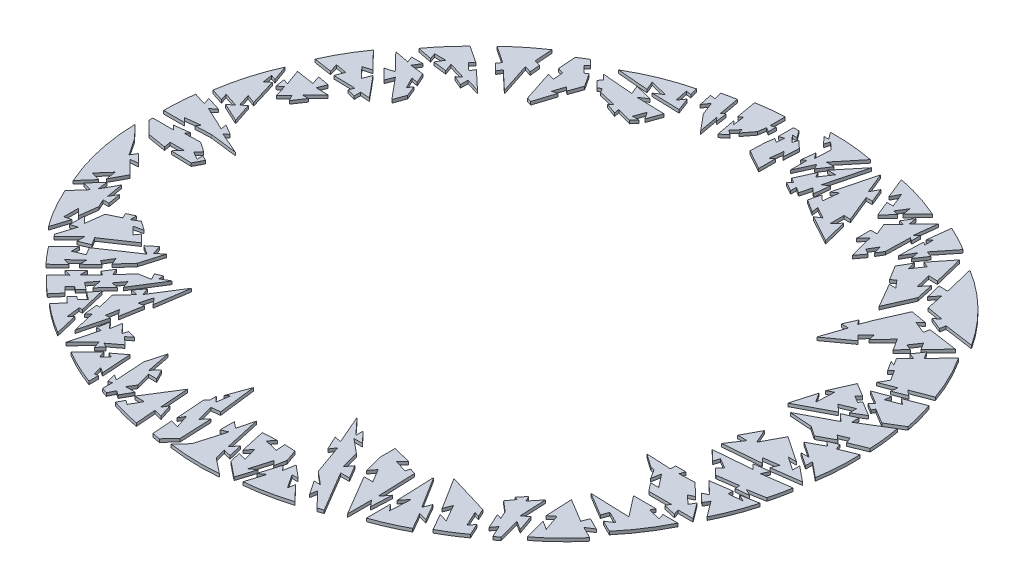
SolidWorks part; units mm, degrees
ref_plane "Front Plane" through (0, 0, 0) normal (0, 0, 1) x (1, 0, 0)
ref_plane "Top Plane" through (0, 0, 0) normal (0, 1, 0) x (1, 0, 0)
ref_plane "Right Plane" through (0, 0, 0) normal (1, 0, 0) x (0, 0, -1)
sketch "Sketch4" plane through (0, 0, 0) normal (0, 1, 0) x (1, 0, 0)
  line L0 (79.5359, 1089.8998) -> (71.878, 1117.1281)
  line L1 (73.9997, 1152.1973) -> (66.3418, 1179.4255)
  line L2 (66.3418, 1179.4255) -> (102.248, 1172.9243)
  line L3 (102.248, 1172.9243) -> (91.5541, 1145.5955)
  line L4 (91.5541, 1145.5955) -> (160.3382, 1144.0112)
  line L5 (160.3382, 1144.0112) -> (154.1634, 1128.2312)
  line L6 (154.1634, 1128.2312) -> (180.6697, 1121.1712)
  line L7 (180.6697, 1121.1712) -> (180.6697, 1142.2375)
  line L8 (73.9997, 1152.1973) -> (16.3638, 1160.9945)
  line L35 (210.6041, 1140.0847) -> (180.6697, 1142.2375)
  line L36 (71.878, 1117.1281) -> (107.7842, 1110.6269)
  line L37 (107.7842, 1110.6269) -> (97.0903, 1083.2981)
  line L38 (97.0903, 1083.2981) -> (135.6348, 1082.4103)
  line L39 (79.5359, 1089.8998) -> (21.9, 1098.6971)
  line L40 (21.9, 1098.6971) -> (40.3394, 1047.8857)
  line L41 (40.3394, 1047.8857) -> (23.558, 1054.1541)
  line L42 (23.558, 1054.1541) -> (28.1022, 1023.4113)
  line L43 (28.1022, 1023.4113) -> (43.8266, 1035.8446)
  line L44 (55.1591, 998.4828) -> (79.5359, 1023.4113)
  line L45 (79.5359, 1023.4113) -> (89.8311, 1004.6435)
  line L64 (89.8311, 1004.6435) -> (114.7462, 1041.0407)
  line L65 (114.7462, 1041.0407) -> (96.117, 1041.0407)
  line L66 (96.117, 1041.0407) -> (135.6348, 1082.4103)
  line L67 (43.8266, 1035.8446) -> (55.1591, 998.4828)
  line L68 (-9.812, 1090.6091) -> (8.6274, 1039.7977)
  line L69 (8.6274, 1039.7977) -> (-8.154, 1046.0661)
  line L70 (-8.154, 1046.0661) -> (-3.6098, 1015.3233)
  line L71 (-3.6098, 1015.3233) -> (12.1146, 1027.7566)
  line L72 (12.1146, 1027.7566) -> (38.0015, 942.4103)
  line L73 (38.0015, 942.4103) -> (9.8008, 952.6982)
  line L74 (9.8008, 952.6982) -> (22.6226, 912.6921)
  line L75 (22.6226, 912.6921) -> (38.0015, 925.5308)
  line L76 (38.0015, 925.5308) -> (58.1191, 864.5278)
  line L77 (58.1191, 864.5278) -> (-1.2858, 891.8241)
  line L78 (-1.2858, 891.8241) -> (16.2019, 906.4232)
  line L79 (16.2019, 906.4232) -> (-28.7199, 920.9974)
  line L80 (-28.7199, 920.9974) -> (-21.3292, 898.5866)
  line L81 (-21.3292, 898.5866) -> (-61.1515, 911.5063)
  line L82 (41.7553, 825.6716) -> (-17.6495, 852.9679)
  line L83 (-17.6495, 852.9679) -> (-0.1619, 867.567)
  line L84 (-0.1619, 867.567) -> (-45.0836, 882.1412)
  line L85 (-45.0836, 882.1412) -> (-37.693, 859.7304)
  line L86 (-37.693, 859.7304) -> (-77.5152, 872.6501)
  line L87 (41.7553, 825.6716) -> (59.7084, 816.3946)
  line L88 (59.7084, 816.3946) -> (55.819, 836.0191)
  line L89 (55.819, 836.0191) -> (88.8123, 816.3946)
  line L90 (88.8123, 816.3946) -> (76.112, 805.7921)
  line L91 (76.112, 805.7921) -> (146.473, 775.3267)
  line L92 (146.473, 775.3267) -> (59.7084, 785.9441)
  line L93 (59.7084, 785.9441) -> (8.8008, 783.9297)
  line L94 (8.8008, 783.9297) -> (17.1872, 795.589)
  line L95 (17.1872, 795.589) -> (-30.9924, 789.7594)
  line L96 (-30.9924, 789.7594) -> (-17.6495, 776.2204)
  line L97 (-17.6495, 776.2204) -> (-83.9589, 776.2204)
  line L98 (63.2013, 747.6353) -> (12.2938, 745.6208)
  line L99 (12.2938, 745.6208) -> (20.6801, 757.2802)
  line L100 (20.6801, 757.2802) -> (-27.4995, 751.4505)
  line L101 (-27.4995, 751.4505) -> (-14.1566, 737.9115)
  line L102 (-14.1566, 737.9115) -> (-80.466, 737.9115)
  line L103 (18.4006, 676.6175) -> (-41.5907, 686.5197)
  line L104 (-41.5907, 686.5197) -> (-80.2858, 725.7594)
  line L105 (18.4006, 676.6175) -> (14.8503, 698.4776)
  line L106 (14.8503, 698.4776) -> (59.312, 698.4776)
  line L107 (59.312, 698.4776) -> (40.2095, 676.6175)
  line L108 (40.2095, 676.6175) -> (105.5647, 675.0282)
  line L109 (121.2047, 705.1335) -> (105.5647, 675.0282)
  line L110 (104.6253, 713.0579) -> (104.6253, 694.5101)
  line L111 (104.6253, 694.5101) -> (79.6049, 708.9291)
  line L112 (79.6049, 708.9291) -> (94.4726, 725.943)
  line L113 (94.4726, 725.943) -> (63.2013, 747.6353)
  line L114 (121.2047, 705.1335) -> (104.6253, 713.0579)
  line L135 (-52.5566, 652.2053) -> (-91.2517, 691.445)
  line L136 (40.5682, 543.7111) -> (-2.8318, 587.3061)
  line L137 (-2.8318, 587.3061) -> (21.9174, 589.3977)
  line L138 (21.9174, 589.3977) -> (-4.7576, 616.1926)
  line L139 (-4.7576, 616.1926) -> (-16.1906, 597.7172)
  line L140 (-16.1906, 597.7172) -> (-52.5566, 652.2053)
  line L141 (-34.3736, 437.3354) -> (3.8844, 480.667)
  line L142 (3.8844, 480.667) -> (-25.1225, 488.2913)
  line L143 (-25.1225, 488.2913) -> (9.5428, 527.5539)
  line L144 (9.5428, 527.5539) -> (14.1648, 495.3898)
  line L145 (14.1648, 495.3898) -> (40.5682, 543.7111)
  line L146 (-19.5714, 396.3307) -> (18.6866, 439.6623)
  line L147 (18.6866, 439.6623) -> (-10.3203, 447.2866)
  line L148 (-10.3203, 447.2866) -> (24.345, 486.5492)
  line L149 (24.345, 486.5492) -> (28.967, 454.3851)
  line L150 (28.967, 454.3851) -> (55.3704, 502.7064)
  line L151 (55.3704, 502.7064) -> (64.4327, 448.5721)
  line L152 (64.4327, 448.5721) -> (78.7344, 472.4331)
  line L153 (78.7344, 472.4331) -> (85.5857, 431.5063)
  line L154 (85.5857, 431.5063) -> (67.0376, 431.5063)
  line L155 (67.0376, 431.5063) -> (78.7344, 406.2208)
  line L156 (78.7344, 406.2208) -> (71.5835, 348.2306)
  line L157 (71.5835, 348.2306) -> (50.9729, 368.1292)
  line L158 (50.9729, 368.1292) -> (50.9729, 321.2253)
  line L159 (50.9729, 321.2253) -> (71.5835, 327.4792)
  line L160 (71.5835, 327.4792) -> (53.6085, 270.245)
  line L161 (109.8229, 394.7287) -> (102.6721, 336.7385)
  line L162 (102.6721, 336.7385) -> (82.0614, 356.6371)
  line L163 (82.0614, 356.6371) -> (82.0614, 309.7332)
  line L164 (82.0614, 309.7332) -> (102.6721, 315.9871)
  line L165 (102.6721, 315.9871) -> (84.6971, 258.7529)
  line L166 (109.8229, 394.7287) -> (148.4258, 413.3028)
  line L167 (148.4258, 413.3028) -> (140.7503, 429.2549)
  line L168 (140.7503, 429.2549) -> (165.1674, 441.0033)
  line L169 (165.1674, 441.0033) -> (165.1674, 420.0142)
  line L170 (165.1674, 420.0142) -> (187.3968, 433.6883)
  line L171 (187.3968, 433.6883) -> (216.5305, 413.3028)
  line L172 (216.5305, 413.3028) -> (188.5529, 406.2811)
  line L173 (188.5529, 406.2811) -> (212.0257, 382.4073)
  line L174 (212.0257, 382.4073) -> (223.3551, 398.5985)
  line L175 (223.3551, 398.5985) -> (247.6934, 373.8445)
  line L176 (158.2649, 313.4244) -> (247.6934, 373.8445)
  line L177 (158.2649, 313.4244) -> (173.1358, 289.2494)
  line L178 (173.1358, 289.2494) -> (139.5784, 275.1033)
  line L179 (139.5784, 275.1033) -> (139.5784, 301.3369)
  line L180 (139.5784, 301.3369) -> (89.5954, 252.1934)
  line L181 (177.3283, 276.8624) -> (287.5603, 351.3379)
  line L182 (177.3283, 276.8624) -> (192.1992, 252.6874)
  line L183 (192.1992, 252.6874) -> (158.6418, 238.5412)
  line L184 (158.6418, 238.5412) -> (158.6418, 264.7749)
  line L185 (158.6418, 264.7749) -> (108.6588, 215.6313)
  line L186 (287.5603, 351.3379) -> (259.2555, 369.719)
  line L187 (259.2555, 369.719) -> (287.0565, 392.6928)
  line L188 (287.0565, 392.6928) -> (295.8178, 363.6402)
  line L189 (295.8178, 363.6402) -> (318.7295, 382.5737)
  line L190 (318.7295, 382.5737) -> (297.3156, 310.6221)
  line L191 (297.3156, 310.6221) -> (259.2555, 268.0309)
  line L192 (259.2555, 268.0309) -> (250.2294, 289.3265)
  line L193 (250.2294, 289.3265) -> (231.0892, 259.1338)
  line L194 (84.2949, 1279.2365) -> (138.6323, 1222.9248)
  line L195 (138.6323, 1222.9248) -> (111.4636, 1214.9972)
  line L196 (111.4636, 1214.9972) -> (143.6719, 1181.6185)
  line L197 (143.6719, 1181.6185) -> (154.1634, 1207.9843)
  line L198 (154.1634, 1207.9843) -> (210.6041, 1140.0847)
  line L199 (231.0892, 259.1338) -> (244.7359, 250.4826)
  line L200 (244.7359, 250.4826) -> (207.6163, 215.6313)
  line L201 (207.6163, 215.6313) -> (207.6163, 238.5412)
  line L202 (207.6163, 238.5412) -> (170.9902, 204.1532)
  line L203 (170.9902, 204.1532) -> (192.2281, 197.8325)
  line L204 (192.2281, 197.8325) -> (153.9045, 161.9312)
  line L205 (327.7031, 282.0513) -> (364.7513, 288.7164)
  line L206 (364.7513, 288.7164) -> (354.124, 308.7117)
  line L207 (354.124, 308.7117) -> (375.3188, 317.2744)
  line L208 (375.3188, 317.2744) -> (375.3188, 302.0466)
  line L209 (375.3188, 302.0466) -> (402.175, 317.2744)
  line L210 (327.7031, 282.0513) -> (289.643, 239.4601)
  line L211 (289.643, 239.4601) -> (280.617, 260.7557)
  line L212 (280.617, 260.7557) -> (261.4767, 230.563)
  line L213 (261.4767, 230.563) -> (275.1235, 221.9118)
  line L214 (275.1235, 221.9118) -> (238.0039, 187.0605)
  line L215 (238.0039, 187.0605) -> (238.0039, 209.9704)
  line L216 (238.0039, 209.9704) -> (201.3777, 175.5824)
  line L217 (201.3777, 175.5824) -> (222.6156, 169.2617)
  line L218 (222.6156, 169.2617) -> (184.292, 133.3604)
  line L219 (402.175, 317.2744) -> (341.8275, 221.9118)
  line L220 (341.8275, 221.9118) -> (333.1879, 244.6003)
  line L221 (333.1879, 244.6003) -> (311.4804, 216.0333)
  line L222 (311.4804, 216.0333) -> (332.3107, 211.7006)
  line L223 (332.3107, 211.7006) -> (294.4375, 171.3508)
  line L224 (287.3953, 201.1846) -> (294.4375, 171.3508)
  line L225 (287.3953, 201.1846) -> (265.9814, 173.004)
  line L226 (265.9814, 173.004) -> (288.2043, 156.1173)
  line L227 (288.2043, 156.1173) -> (271.5121, 138.3335)
  line L228 (271.5121, 138.3335) -> (261.4767, 145.9592)
  line L229 (261.4767, 145.9592) -> (246.1918, 129.6748)
  line L230 (246.1918, 129.6748) -> (264.3109, 112.6678)
  line L231 (264.3109, 112.6678) -> (238.114, 81.973)
  line L232 (318.166, 177.3401) -> (337.8259, 94.0532)
  line L233 (318.166, 177.3401) -> (296.7522, 149.1595)
  line L234 (296.7522, 149.1595) -> (318.975, 132.2728)
  line L235 (318.975, 132.2728) -> (302.2828, 114.489)
  line L236 (302.2828, 114.489) -> (292.2474, 122.1147)
  line L237 (292.2474, 122.1147) -> (276.9626, 105.8303)
  line L238 (276.9626, 105.8303) -> (295.0817, 88.8234)
  line L239 (295.0817, 88.8234) -> (268.8848, 58.1285)
  line L240 (337.8259, 94.0532) -> (327.9151, 94.0532)
  line L241 (327.9151, 94.0532) -> (332.8705, 49.6725)
  line L242 (332.8705, 49.6725) -> (344.9741, 63.7705)
  line L243 (344.9741, 63.7705) -> (362.023, -8.4551)
  line L244 (440.4983, 119.8912) -> (434.3623, 83.8629)
  line L245 (434.3623, 83.8629) -> (416.9707, 104.6379)
  line L246 (416.9707, 104.6379) -> (410.558, 66.9847)
  line L247 (410.558, 66.9847) -> (425.6665, 66.9847)
  line L248 (425.6665, 66.9847) -> (402.5678, -22.3111)
  line L249 (454.3684, 31.6376) -> (402.5678, -22.3111)
  line L250 (454.3684, 31.6376) -> (461.7886, 9.1427)
  line L251 (461.7886, 9.1427) -> (480.2454, 28.3649)
  line L252 (480.2454, 28.3649) -> (465.6489, 35.8165)
  line L253 (465.6489, 35.8165) -> (503.6435, 64.677)
  line L254 (503.6435, 64.677) -> (480.2454, 87.1434)
  line L255 (480.2454, 87.1434) -> (498.0043, 100.633)
  line L256 (498.0043, 100.633) -> (472.9472, 108.2587)
  line L257 (472.9472, 108.2587) -> (467.859, 91.5396)
  line L258 (467.859, 91.5396) -> (440.4983, 119.8912)
  line L259 (453.5868, 328.4896) -> (393.2394, 233.127)
  line L260 (393.2394, 233.127) -> (384.5998, 255.8155)
  line L261 (384.5998, 255.8155) -> (362.8923, 227.2485)
  line L262 (362.8923, 227.2485) -> (383.7226, 222.9158)
  line L263 (383.7226, 222.9158) -> (345.8494, 182.566)
  line L264 (345.8494, 182.566) -> (358.4671, 129.1129)
  line L265 (358.4671, 129.1129) -> (348.5562, 129.1129)
  line L266 (348.5562, 129.1129) -> (353.5116, 84.7321)
  line L267 (353.5116, 84.7321) -> (365.6153, 98.8302)
  line L268 (365.6153, 98.8302) -> (382.6642, 26.6045)
  line L269 (453.5868, 328.4896) -> (437.3752, 221.1856)
  line L270 (437.3752, 221.1856) -> (420.1363, 241.7782)
  line L271 (420.1363, 241.7782) -> (408.781, 201.354)
  line L272 (408.781, 201.354) -> (426.7307, 204.8352)
  line L273 (426.7307, 204.8352) -> (414.4587, 132.7786)
  line L274 (414.4587, 132.7786) -> (397.0671, 153.5535)
  line L275 (397.0671, 153.5535) -> (390.6544, 115.9004)
  line L276 (390.6544, 115.9004) -> (405.7629, 115.9004)
  line L277 (405.7629, 115.9004) -> (382.6642, 26.6045)
  line L278 (489.7421, 12.2739) -> (437.9415, -41.6748)
  line L279 (489.7421, 12.2739) -> (497.1624, -10.221)
  line L280 (497.1624, -10.221) -> (515.6191, 9.0012)
  line L281 (515.6191, 9.0012) -> (501.0227, 16.4528)
  line L282 (501.0227, 16.4528) -> (539.0172, 45.3134)
  line L283 (539.0172, 45.3134) -> (545.1565, -48.1271)
  line L284 (545.1565, -48.1271) -> (528.2486, -37.3245)
  line L285 (528.2486, -37.3245) -> (535.5641, -65.1355)
  line L286 (535.5641, -65.1355) -> (546.7364, -62.1968)
  line L287 (546.7364, -62.1968) -> (546.7364, -93.4831)
  line L288 (597.756, 108.0004) -> (581.0328, 47.2511)
  line L289 (581.0328, 47.2511) -> (587.1721, -46.1894)
  line L290 (587.1721, -46.1894) -> (570.2643, -35.3868)
  line L291 (570.2643, -35.3868) -> (577.5797, -63.1978)
  line L292 (577.5797, -63.1978) -> (588.752, -60.259)
  line L293 (588.752, -60.259) -> (588.752, -91.5454)
  line L294 (606.8822, -97.9517) -> (617.9056, -75.6525)
  line L295 (617.9056, -75.6525) -> (631.3095, -85.1148)
  line L296 (631.3095, -85.1148) -> (651.3371, -49.9464)
  line L297 (651.3371, -49.9464) -> (620.7429, -49.9464)
  line L298 (620.7429, -49.9464) -> (635.6983, -26.1224)
  line L299 (597.756, 108.0004) -> (612.6601, 32.4885)
  line L300 (612.6601, 32.4885) -> (632.4593, 53.6124)
  line L301 (632.4593, 53.6124) -> (648.8369, 21.3093)
  line L302 (648.8369, 21.3093) -> (622.5597, 21.3093)
  line L303 (622.5597, 21.3093) -> (635.6983, -26.1224)
  line L304 (647.7806, -109.7054) -> (658.804, -87.4062)
  line L305 (658.804, -87.4062) -> (672.2079, -96.8685)
  line L306 (672.2079, -96.8685) -> (692.2355, -61.7001)
  line L307 (692.2355, -61.7001) -> (661.6413, -61.7001)
  line L308 (661.6413, -61.7001) -> (726.6499, 41.8587)
  line L309 (726.6499, 41.8587) -> (733.4955, -51.4908)
  line L310 (733.4955, -51.4908) -> (744.7171, -31.7858)
  line L311 (744.7171, -31.7858) -> (758.6307, -74.9515)
  line L312 (758.6307, -74.9515) -> (733.4955, -68.6384)
  line L313 (733.4955, -68.6384) -> (738.2376, -133.3031)
  line L314 (782.5526, 38.6884) -> (789.3982, -54.6612)
  line L315 (789.3982, -54.6612) -> (800.6198, -34.9561)
  line L316 (800.6198, -34.9561) -> (814.5334, -78.1219)
  line L317 (814.5334, -78.1219) -> (789.3982, -71.8088)
  line L318 (789.3982, -71.8088) -> (794.1403, -136.4735)
  line L319 (782.5526, 38.6884) -> (792.499, 47.8472)
  line L320 (792.499, 47.8472) -> (792.499, 68.283)
  line L321 (792.499, 68.283) -> (807.9228, 51.5329)
  line L322 (807.9228, 51.5329) -> (814.5334, 93.0764)
  line L323 (814.5334, 93.0764) -> (802.5788, 82.0683)
  line L324 (802.5788, 82.0683) -> (827.7928, 151.8613)
  line L325 (827.7928, 151.8613) -> (842.5112, 32.327)
  line L326 (842.5112, 32.327) -> (814.5334, 28.8821)
  line L327 (814.5334, 28.8821) -> (828.5223, -23.2073)
  line L328 (828.5223, -23.2073) -> (846.939, -3.6329)
  line L329 (846.939, -3.6329) -> (851.2656, -106.4695)
  line L330 (851.2656, -106.4695) -> (819.0982, -140.659)
  line L331 (884.602, -102.3334) -> (852.4346, -136.523)
  line L332 (1011.3991, -140.9469) -> (963.0536, -102.3334)
  line L333 (963.0536, -102.3334) -> (954.3483, -67.6727)
  line L334 (954.3483, -67.6727) -> (979.2244, -73.9858)
  line L335 (979.2244, -73.9858) -> (968.3831, -30.8201)
  line L336 (968.3831, -30.8201) -> (951.1449, -52.4029)
  line L337 (951.1449, -52.4029) -> (925.3875, 63.3256)
  line L338 (925.3875, 63.3256) -> (911.9868, 10.5214)
  line L339 (911.9868, 10.5214) -> (891.5946, 26.8085)
  line L340 (891.5946, 26.8085) -> (891.5946, -19.0713)
  line L341 (891.5946, -19.0713) -> (911.9868, -9.6421)
  line L342 (911.9868, -9.6421) -> (884.602, -102.3334)
  line L343 (1044.5789, -126.9573) -> (996.2333, -88.3438)
  line L344 (996.2333, -88.3438) -> (987.5281, -53.6831)
  line L345 (987.5281, -53.6831) -> (1012.4042, -59.9962)
  line L346 (1012.4042, -59.9962) -> (1001.5629, -16.8305)
  line L347 (1001.5629, -16.8305) -> (984.3247, -38.4133)
  line L348 (984.3247, -38.4133) -> (966.6948, 40.7981)
  line L349 (1069.9912, 42.4) -> (1083.4627, 4.3475)
  line L350 (1083.4627, 4.3475) -> (1076.7177, -32.1852)
  line L351 (1076.7177, -32.1852) -> (1063.0141, -16.8305)
  line L352 (1063.0141, -16.8305) -> (1043.786, -81.9132)
  line L353 (1043.786, -81.9132) -> (1063.0141, -68.0416)
  line L354 (1063.0141, -68.0416) -> (1044.5789, -126.9573)
  line L355 (966.6948, 40.7981) -> (1012.4042, 44.0018)
  line L356 (1012.4042, 44.0018) -> (996.2333, 24.5109)
  line L357 (996.2333, 24.5109) -> (1038.0939, 14.4927)
  line L358 (1038.0939, 14.4927) -> (1036.0257, 44.0018)
  line L359 (1036.0257, 44.0018) -> (1069.9912, 42.4)
  line L360 (1110.8077, 5.503) -> (1104.0626, -31.0296)
  line L361 (1104.0626, -31.0296) -> (1090.359, -15.6749)
  line L362 (1090.359, -15.6749) -> (1071.131, -80.7577)
  line L363 (1071.131, -80.7577) -> (1090.359, -66.886)
  line L364 (1090.359, -66.886) -> (1071.9239, -125.8017)
  line L365 (1110.8077, 5.503) -> (1151.1002, -28.12)
  line L366 (1151.1002, -28.12) -> (1130.954, -28.12)
  line L367 (1130.954, -28.12) -> (1160.0657, -71.2953)
  line L368 (1160.0657, -71.2953) -> (1164.0515, -49.7077)
  line L369 (1164.0515, -49.7077) -> (1210.4222, -98.0808)
  line L370 (1076.2683, 235.2613) -> (1116.7409, 141.4578)
  line L371 (1116.7409, 141.4578) -> (1095.947, 145.297)
  line L372 (1095.947, 145.297) -> (1116.7409, 100.7247)
  line L373 (1116.7409, 100.7247) -> (1129.5655, 119.4831)
  line L374 (1129.5655, 119.4831) -> (1163.4977, 23.6366)
  line L375 (1163.4977, 23.6366) -> (1203.7902, -9.9864)
  line L376 (1203.7902, -9.9864) -> (1183.644, -9.9864)
  line L377 (1183.644, -9.9864) -> (1212.7557, -53.1617)
  line L378 (1212.7557, -53.1617) -> (1216.7415, -31.574)
  line L379 (1216.7415, -31.574) -> (1263.1122, -79.9472)
  line L380 (1280.3407, -74.2932) -> (1203.7902, 54.9793)
  line L381 (1203.7902, 54.9793) -> (1231.8985, 54.9793)
  line L382 (1231.8985, 54.9793) -> (1206.6199, 97.6679)
  line L383 (1206.6199, 97.6679) -> (1190.6172, 76.3236)
  line L384 (1190.6172, 76.3236) -> (1175.4344, 133.7856)
  line L385 (1175.4344, 133.7856) -> (1129.5655, 171.5201)
  line L386 (1129.5655, 171.5201) -> (1156.7526, 171.5201)
  line L387 (1156.7526, 171.5201) -> (1123.821, 206.8244)
  line L388 (1123.821, 206.8244) -> (1123.821, 183.3976)
  line L389 (1123.821, 183.3976) -> (1076.2683, 235.2613)
  line L390 (1328.2533, -47.5513) -> (1251.7029, 81.7211)
  line L391 (1251.7029, 81.7211) -> (1279.8112, 81.7211)
  line L392 (1279.8112, 81.7211) -> (1254.5325, 124.4097)
  line L393 (1254.5325, 124.4097) -> (1238.5299, 103.0654)
  line L394 (1238.5299, 103.0654) -> (1223.3471, 160.5274)
  line L395 (1328.2533, -47.5513) -> (1328.2533, 29.2005)
  line L396 (1328.2533, 29.2005) -> (1345.2819, 9.4955)
  line L397 (1345.2819, 9.4955) -> (1348.3643, 76.0791)
  line L398 (1348.3643, 76.0791) -> (1328.2533, 50.3785)
  line L399 (1328.2533, 50.3785) -> (1323.5175, 172.0388)
  line L400 (1323.5175, 172.0388) -> (1305.4299, 177.4734)
  line L401 (1305.4299, 177.4734) -> (1301.2732, 163.6391)
  line L402 (1301.2732, 163.6391) -> (1260.6684, 175.8392)
  line L403 (1260.6684, 175.8392) -> (1280.9301, 195.2907)
  line L404 (1280.9301, 195.2907) -> (1223.3471, 210.1394)
  line L405 (1223.3471, 160.5274) -> (1223.3471, 210.1394)
  line L406 (1370.2147, -28.8543) -> (1370.2147, 47.8976)
  line L407 (1370.2147, 47.8976) -> (1387.2432, 28.1926)
  line L408 (1387.2432, 28.1926) -> (1390.3257, 94.7762)
  line L409 (1390.3257, 94.7762) -> (1370.2147, 69.0756)
  line L410 (1370.2147, 69.0756) -> (1365.4788, 190.7359)
  line L411 (1365.4788, 190.7359) -> (1429.0622, 89.239)
  line L412 (1429.0622, 89.239) -> (1439.1849, 115.1807)
  line L413 (1439.1849, 115.1807) -> (1470.0401, 61.4844)
  line L414 (1470.0401, 61.4844) -> (1442.7514, 69.0756)
  line L415 (1442.7514, 69.0756) -> (1473.0067, 16.4233)
  line L416 (1400.9661, 220.3988) -> (1464.5495, 118.9019)
  line L417 (1464.5495, 118.9019) -> (1474.6721, 144.8436)
  line L418 (1474.6721, 144.8436) -> (1505.5274, 91.1473)
  line L419 (1505.5274, 91.1473) -> (1478.2386, 98.7385)
  line L420 (1478.2386, 98.7385) -> (1508.494, 46.0863)
  line L421 (1532.7607, 180.7996) -> (1544.5319, 155.1339)
  line L422 (1544.5319, 155.1339) -> (1528.505, 160.3638)
  line L423 (1528.505, 160.3638) -> (1550.7762, 111.8042)
  line L424 (1550.7762, 111.8042) -> (1564.4925, 130.0811)
  line L425 (1564.4925, 130.0811) -> (1581.7569, 92.4382)
  line L426 (1532.7607, 180.7996) -> (1400.9661, 220.3988)
  line L427 (1574.3271, 210.7666) -> (1586.0983, 185.101)
  line L428 (1586.0983, 185.101) -> (1570.0714, 190.3308)
  line L429 (1570.0714, 190.3308) -> (1592.3426, 141.7712)
  line L430 (1592.3426, 141.7712) -> (1606.0589, 160.0481)
  line L431 (1606.0589, 160.0481) -> (1623.3233, 122.4052)
  line L432 (1574.3271, 210.7666) -> (1541.8504, 238.4099)
  line L433 (1606.0589, 307.483) -> (1578.4235, 273.6177)
  line L434 (1578.4235, 273.6177) -> (1570.0714, 290.5504)
  line L435 (1570.0714, 290.5504) -> (1550.0808, 266.0532)
  line L436 (1550.0808, 266.0532) -> (1560.0761, 263.6974)
  line L437 (1560.0761, 263.6974) -> (1541.8504, 238.4099)
  line L438 (1638.5754, 133.8409) -> (1620.1147, 202.7368)
  line L439 (1620.1147, 202.7368) -> (1648.0171, 185.101)
  line L440 (1648.0171, 185.101) -> (1629.3451, 238.4099)
  line L441 (1629.3451, 238.4099) -> (1610.1228, 222.8264)
  line L442 (1610.1228, 222.8264) -> (1606.0589, 307.483)
  line L443 (1679.6101, 176.3637) -> (1661.1494, 245.2596)
  line L444 (1661.1494, 245.2596) -> (1689.0517, 227.6238)
  line L445 (1689.0517, 227.6238) -> (1670.3797, 280.9328)
  line L446 (1670.3797, 280.9328) -> (1651.1574, 265.3493)
  line L447 (1651.1574, 265.3493) -> (1647.0935, 350.0059)
  line L448 (1647.0935, 350.0059) -> (1721.9473, 305.0948)
  line L449 (1721.9473, 305.0948) -> (1730.3224, 327.5503)
  line L450 (1730.3224, 327.5503) -> (1768.1103, 308.5761)
  line L451 (1768.1103, 308.5761) -> (1744.1218, 292.8887)
  line L452 (1744.1218, 292.8887) -> (1781.644, 274.0478)
  line L453 (1735.6758, 460.2851) -> (1786.9133, 394.4206)
  line L454 (1786.9133, 394.4206) -> (1660.8221, 398.9075)
  line L455 (1882.5379, 455.3618) -> (1834.6764, 455.3618)
  line L456 (1834.6764, 455.3618) -> (1840.4702, 437.6367)
  line L457 (1840.4702, 437.6367) -> (1800.7038, 446.4993)
  line L458 (1800.7038, 446.4993) -> (1807.8143, 460.2851)
  line L459 (1807.8143, 460.2851) -> (1735.6758, 460.2851)
  line L460 (1660.8221, 398.9075) -> (1735.6758, 353.9964)
  line L461 (1735.6758, 353.9964) -> (1744.0509, 376.4519)
  line L462 (1744.0509, 376.4519) -> (1781.8388, 357.4777)
  line L463 (1781.8388, 357.4777) -> (1757.8503, 341.7903)
  line L464 (1757.8503, 341.7903) -> (1795.3726, 322.9494)
  line L465 (1684.3269, 567.2579) -> (1696.442, 565.488)
  line L466 (1696.442, 565.488) -> (1714.701, 536.1045)
  line L467 (1714.701, 536.1045) -> (1720.341, 565.488)
  line L468 (1720.341, 565.488) -> (1753.0451, 523.4477)
  line L469 (1753.0451, 523.4477) -> (1727.1065, 523.4477)
  line L470 (1727.1065, 523.4477) -> (1747.5966, 497.1081)
  line L471 (1641.0111, 597.6249) -> (1684.3269, 567.2579)
  line L472 (1894.4587, 492.1848) -> (1846.5972, 492.1848)
  line L473 (1846.5972, 492.1848) -> (1852.391, 474.4597)
  line L474 (1852.391, 474.4597) -> (1812.6246, 483.3223)
  line L475 (1812.6246, 483.3223) -> (1819.7351, 497.1081)
  line L476 (1819.7351, 497.1081) -> (1747.5966, 497.1081)
  line L477 (1894.4587, 492.1848) -> (1857.3442, 541.8288)
  line L478 (1857.3442, 541.8288) -> (1846.5972, 523.4477)
  line L479 (1846.5972, 523.4477) -> (1819.7351, 548.8505)
  line L480 (1819.7351, 548.8505) -> (1837.3798, 557.4161)
  line L481 (1837.3798, 557.4161) -> (1796.8762, 595.7194)
  line L482 (1641.0111, 597.6249) -> (1720.341, 593.8139)
  line L483 (1720.341, 593.8139) -> (1720.341, 610.2642)
  line L484 (1720.341, 610.2642) -> (1753.0451, 610.2642)
  line L485 (1753.0451, 610.2642) -> (1747.5966, 593.8139)
  line L486 (1747.5966, 593.8139) -> (1796.8762, 595.7194)
  line L487 (1911.8649, 519.3218) -> (1874.7505, 568.9658)
  line L488 (1874.7505, 568.9658) -> (1864.0034, 550.5846)
  line L489 (1864.0034, 550.5846) -> (1837.1414, 575.9875)
  line L490 (1837.1414, 575.9875) -> (1854.7861, 584.553)
  line L491 (1854.7861, 584.553) -> (1814.2825, 622.8564)
  line L492 (1881.8619, 632.234) -> (1881.8619, 616.7978)
  line L493 (1881.8619, 616.7978) -> (1924.8748, 620.9509)
  line L494 (1924.8748, 620.9509) -> (1903.3683, 632.234)
  line L495 (1903.3683, 632.234) -> (1958.6347, 641.7743)
  line L496 (1814.2825, 622.8564) -> (1881.8619, 632.234)
  line L497 (1810.1127, 648.9588) -> (1790.1081, 667.8767)
  line L498 (1790.1081, 667.8767) -> (1804.5325, 683.1297)
  line L499 (1804.5325, 683.1297) -> (1772.0136, 702.1427)
  line L500 (1772.0136, 702.1427) -> (1766.2816, 683.1297)
  line L501 (1766.2816, 683.1297) -> (1733.5774, 714.0573)
  line L502 (1877.692, 658.3364) -> (1877.692, 642.9002)
  line L503 (1877.692, 642.9002) -> (1920.705, 647.0533)
  line L504 (1920.705, 647.0533) -> (1899.1985, 658.3364)
  line L505 (1899.1985, 658.3364) -> (1954.4649, 667.8767)
  line L506 (1810.1127, 648.9588) -> (1877.692, 658.3364)
  line L507 (1969.4631, 737.0668) -> (1877.692, 724.3323)
  line L508 (1877.692, 724.3323) -> (1887.4094, 746.8746)
  line L509 (1887.4094, 746.8746) -> (1838.2978, 740.0597)
  line L510 (1838.2978, 740.0597) -> (1853.376, 724.3323)
  line L511 (1853.376, 724.3323) -> (1733.5774, 714.0573)
  line L512 (1967.5266, 769.0904) -> (1875.7555, 756.3558)
  line L513 (1875.7555, 756.3558) -> (1885.4729, 778.8982)
  line L514 (1885.4729, 778.8982) -> (1836.3612, 772.0832)
  line L515 (1836.3612, 772.0832) -> (1851.4395, 756.3558)
  line L516 (1851.4395, 756.3558) -> (1731.6409, 746.0808)
  line L517 (1731.6409, 746.0808) -> (1764.345, 794.5808)
  line L518 (1764.345, 794.5808) -> (1734.8449, 794.5808)
  line L519 (1734.8449, 794.5808) -> (1764.345, 850.0748)
  line L520 (1764.345, 850.0748) -> (1784.5305, 805.8321)
  line L521 (1784.5305, 805.8321) -> (1819.1823, 871.0172)
  line L522 (1819.1823, 871.0172) -> (1901.8115, 815.2994)
  line L523 (1901.8115, 815.2994) -> (1875.7555, 815.2994)
  line L524 (1875.7555, 815.2994) -> (1918.7684, 786.2953)
  line L525 (1918.7684, 786.2953) -> (1918.7684, 808.8789)
  line L526 (1918.7684, 808.8789) -> (1967.5266, 769.0904)
  line L527 (1860.1835, 881.5515) -> (1910.5554, 847.585)
  line L528 (1910.5554, 847.585) -> (1884.4995, 847.585)
  line L529 (1884.4995, 847.585) -> (1927.5124, 818.5809)
  line L530 (1927.5124, 818.5809) -> (1927.5124, 841.1645)
  line L531 (1927.5124, 841.1645) -> (1976.2706, 801.376)
  line L532 (1984.2379, 936.4209) -> (1930.8447, 914.4706)
  line L533 (1930.8447, 914.4706) -> (1923.471, 932.4069)
  line L534 (1923.471, 932.4069) -> (1894.2169, 920.3803)
  line L535 (1894.2169, 920.3803) -> (1908.8439, 908.0157)
  line L536 (1908.8439, 908.0157) -> (1860.1835, 881.5515)
  line L537 (1725.9126, 964.0161) -> (1832.2092, 1019.9958)
  line L538 (1832.2092, 1019.9958) -> (1808.8399, 1041.0191)
  line L539 (1808.8399, 1041.0191) -> (1851.2944, 1058.694)
  line L540 (1851.2944, 1058.694) -> (1851.2944, 1035.4058)
  line L541 (1851.2944, 1035.4058) -> (1889.6326, 1058.6564)
  line L542 (1725.9126, 964.0161) -> (1747.8819, 1041.0191)
  line L543 (1747.8819, 1041.0191) -> (1768.0296, 1010.8859)
  line L544 (1768.0296, 1010.8859) -> (1770.6085, 1068.8342)
  line L545 (1770.6085, 1068.8342) -> (1751.9106, 1058.694)
  line L546 (1751.9106, 1058.694) -> (1782.8644, 1129.0422)
  line L547 (1782.8644, 1129.0422) -> (1826.4846, 1102.729)
  line L548 (1826.868, 937.1464) -> (1859.1251, 915.395)
  line L549 (1755.7934, 941.8592) -> (1826.868, 937.1464)
  line L550 (1983.1796, 970.2644) -> (1929.7864, 948.3141)
  line L551 (1929.7864, 948.3141) -> (1922.4127, 966.2504)
  line L552 (1922.4127, 966.2504) -> (1893.1585, 954.2238)
  line L553 (1893.1585, 954.2238) -> (1907.7856, 941.8592)
  line L554 (1907.7856, 941.8592) -> (1859.1251, 915.395)
  line L555 (1755.7934, 941.8592) -> (1862.09, 997.8388)
  line L556 (1862.09, 997.8388) -> (1838.7207, 1018.8621)
  line L557 (1838.7207, 1018.8621) -> (1881.1752, 1036.5371)
  line L558 (1881.1752, 1036.5371) -> (1881.1752, 1013.2488)
  line L559 (1881.1752, 1013.2488) -> (1971.7274, 1068.1652)
  line L560 (1826.4846, 1102.729) -> (1814.1661, 1090.3221)
  line L561 (1814.1661, 1090.3221) -> (1835.702, 1077.331)
  line L562 (1835.702, 1077.331) -> (1841.8313, 1087.4917)
  line L563 (1841.8313, 1087.4917) -> (1889.6326, 1058.6564)
  line L564 (1824.3671, 1129.5565) -> (1873.712, 1148.4939)
  line L565 (1873.712, 1148.4939) -> (1870.7471, 1127.5982)
  line L566 (1870.7471, 1127.5982) -> (1912.9471, 1143.7936)
  line L567 (1912.9471, 1143.7936) -> (1895.0631, 1158.0306)
  line L568 (1895.0631, 1158.0306) -> (1958.8215, 1182.4995)
  line L569 (1931.1353, 1059.1708) -> (1983.3494, 1090.8365)
  line L570 (1824.3671, 1129.5565) -> (1867.9873, 1103.2434)
  line L571 (1867.9873, 1103.2434) -> (1855.6688, 1090.8365)
  line L572 (1855.6688, 1090.8365) -> (1877.2047, 1077.8453)
  line L573 (1877.2047, 1077.8453) -> (1883.334, 1088.0061)
  line L574 (1883.334, 1088.0061) -> (1931.1353, 1059.1708)
  line L575 (1874.1404, 1361.7653) -> (1820.1334, 1305.9795)
  line L576 (1820.1334, 1305.9795) -> (1806.4117, 1327.5541)
  line L577 (1806.4117, 1327.5541) -> (1784.8832, 1295.7166)
  line L578 (1784.8832, 1295.7166) -> (1803.5386, 1288.325)
  line L579 (1803.5386, 1288.325) -> (1776.5149, 1260.4113)
  line L580 (1776.5149, 1260.4113) -> (1790.0268, 1239.1666)
  line L581 (1790.0268, 1239.1666) -> (1775.5733, 1244.8932)
  line L582 (1775.5733, 1244.8932) -> (1795.721, 1213.2149)
  line L583 (1795.721, 1213.2149) -> (1806.4083, 1224.2542)
  line L584 (1806.4083, 1224.2542) -> (1826.8945, 1192.0437)
  line L585 (1826.8945, 1192.0437) -> (1810.5558, 1163.5697)
  line L586 (1810.5558, 1163.5697) -> (1859.9007, 1182.5071)
  line L587 (1859.9007, 1182.5071) -> (1856.9358, 1161.6114)
  line L588 (1856.9358, 1161.6114) -> (1899.1358, 1177.8067)
  line L589 (1899.1358, 1177.8067) -> (1881.2518, 1192.0437)
  line L590 (1881.2518, 1192.0437) -> (1945.0102, 1216.5127)
  line L591 (1671.3801, 1415.9719) -> (1723.861, 1407.0041)
  line L592 (1723.861, 1407.0041) -> (1707.3941, 1392.4435)
  line L593 (1707.3941, 1392.4435) -> (1746.7719, 1376.8414)
  line L594 (1746.7719, 1376.8414) -> (1749.859, 1394.908)
  line L595 (1749.859, 1394.908) -> (1844.3974, 1381.4941)
  line L596 (1844.3974, 1381.4941) -> (1790.3903, 1325.7082)
  line L597 (1790.3903, 1325.7082) -> (1776.6687, 1347.2829)
  line L598 (1776.6687, 1347.2829) -> (1755.1401, 1315.4453)
  line L599 (1755.1401, 1315.4453) -> (1773.7955, 1308.0537)
  line L600 (1773.7955, 1308.0537) -> (1746.7719, 1280.14)
  line L601 (1671.3801, 1415.9719) -> (1633.5386, 1329.8668)
  line L602 (1746.7719, 1280.14) -> (1723.861, 1316.1629)
  line L603 (1723.861, 1316.1629) -> (1679.4776, 1270.3177)
  line L604 (1679.4776, 1270.3177) -> (1675.2335, 1290.345)
  line L605 (1675.2335, 1290.345) -> (1649.8157, 1264.09)
  line L606 (1649.8157, 1264.09) -> (1665.5881, 1248.8206)
  line L607 (1665.5881, 1248.8206) -> (1588.8569, 1193.4066)
  line L608 (1588.8569, 1193.4066) -> (1614.457, 1269.076)
  line L609 (1614.457, 1269.076) -> (1591.9304, 1269.076)
  line L610 (1591.9304, 1269.076) -> (1609.0603, 1308.0537)
  line L611 (1609.0603, 1308.0537) -> (1619.7584, 1293.2403)
  line L612 (1619.7584, 1293.2403) -> (1633.5386, 1329.8668)
  line L613 (1648.7206, 1623.6934) -> (1671.6418, 1529.6096)
  line L614 (1671.6418, 1529.6096) -> (1643.2463, 1530.3543)
  line L615 (1643.2463, 1530.3543) -> (1655.0175, 1482.0374)
  line L616 (1655.0175, 1482.0374) -> (1674.9781, 1507.1112)
  line L617 (1674.9781, 1507.1112) -> (1686.5621, 1452.448)
  line L618 (1686.5621, 1452.448) -> (1739.0431, 1443.4802)
  line L619 (1739.0431, 1443.4802) -> (1722.5762, 1428.9197)
  line L620 (1722.5762, 1428.9197) -> (1761.9539, 1413.3176)
  line L621 (1761.9539, 1413.3176) -> (1765.0411, 1431.3841)
  line L622 (1765.0411, 1431.3841) -> (1859.5794, 1417.9702)
  line L623 (1603.7365, 1378.2365) -> (1559.0549, 1455.3737)
  line L624 (1559.0549, 1455.3737) -> (1579.6899, 1455.3737)
  line L625 (1579.6899, 1455.3737) -> (1559.0549, 1479.6314)
  line L626 (1559.0549, 1479.6314) -> (1546.4171, 1468.881)
  line L627 (1546.4171, 1468.881) -> (1517.8001, 1515.3255)
  line L628 (1517.8001, 1515.3255) -> (1540.1736, 1554.3167)
  line L629 (1540.1736, 1554.3167) -> (1546.4171, 1528.6894)
  line L630 (1546.4171, 1528.6894) -> (1571.0289, 1565.0867)
  line L631 (1571.0289, 1565.0867) -> (1553.2278, 1572.1398)
  line L632 (1553.2278, 1572.1398) -> (1603.7365, 1635.5869)
  line L633 (1603.7365, 1635.5869) -> (1626.6577, 1541.5031)
  line L634 (1626.6577, 1541.5031) -> (1598.2622, 1542.2478)
  line L635 (1598.2622, 1542.2478) -> (1610.0334, 1493.9309)
  line L636 (1610.0334, 1493.9309) -> (1629.994, 1519.0047)
  line L637 (1629.994, 1519.0047) -> (1641.5781, 1464.3415)
  line L638 (1641.5781, 1464.3415) -> (1603.7365, 1378.2365)
  line L639 (1503.3658, 1710.5183) -> (1494.7305, 1637.0665)
  line L640 (1494.7305, 1637.0665) -> (1506.9814, 1649.528)
  line L641 (1506.9814, 1649.528) -> (1506.9814, 1621.2115)
  line L642 (1506.9814, 1621.2115) -> (1496.7757, 1627.4911)
  line L643 (1496.7757, 1627.4911) -> (1494.7305, 1549.5087)
  line L644 (1494.7305, 1549.5087) -> (1517.104, 1588.4999)
  line L645 (1517.104, 1588.4999) -> (1523.3475, 1562.8726)
  line L646 (1523.3475, 1562.8726) -> (1547.9593, 1599.2698)
  line L647 (1547.9593, 1599.2698) -> (1530.1582, 1606.3229)
  line L648 (1530.1582, 1606.3229) -> (1580.6669, 1669.7701)
  line L649 (1461.4246, 1540.1102) -> (1448.2287, 1518.7157)
  line L650 (1448.2287, 1518.7157) -> (1440.9627, 1543.7894)
  line L651 (1440.9627, 1543.7894) -> (1423.7487, 1515.8801)
  line L652 (1423.7487, 1515.8801) -> (1440.9627, 1505.2628)
  line L653 (1440.9627, 1505.2628) -> (1419.5072, 1476.5473)
  line L654 (1419.5072, 1476.5473) -> (1399.6946, 1553.4742)
  line L655 (1399.6946, 1553.4742) -> (1379.244, 1530.7091)
  line L656 (1379.244, 1530.7091) -> (1379.244, 1575.5429)
  line L657 (1379.244, 1575.5429) -> (1399.6946, 1575.5429)
  line L658 (1399.6946, 1575.5429) -> (1384.9213, 1611.8131)
  line L659 (1384.9213, 1611.8131) -> (1416.0953, 1643.523)
  line L660 (1416.0953, 1643.523) -> (1399.6946, 1648.0276)
  line L661 (1399.6946, 1648.0276) -> (1419.5072, 1680.2271)
  line L662 (1419.5072, 1680.2271) -> (1423.7487, 1654.0127)
  line L663 (1423.7487, 1654.0127) -> (1470.0599, 1701.1199)
  line L664 (1470.0599, 1701.1199) -> (1461.4246, 1627.6681)
  line L665 (1461.4246, 1627.6681) -> (1473.6755, 1640.1295)
  line L666 (1473.6755, 1640.1295) -> (1473.6755, 1611.8131)
  line L667 (1473.6755, 1611.8131) -> (1463.4698, 1618.0927)
  line L668 (1463.4698, 1618.0927) -> (1461.4246, 1540.1102)
  line L669 (1348.0311, 1629.7314) -> (1328.1422, 1678.5608)
  line L670 (1328.1422, 1678.5608) -> (1348.0311, 1678.5608)
  line L671 (1348.0311, 1678.5608) -> (1329.4956, 1724.0676)
  line L672 (1329.4956, 1724.0676) -> (1315.3476, 1698.1454)
  line L673 (1315.3476, 1698.1454) -> (1288.2143, 1764.7607)
  line L674 (1348.0311, 1629.7314) -> (1379.2051, 1661.4413)
  line L675 (1379.2051, 1661.4413) -> (1362.8044, 1665.9459)
  line L676 (1362.8044, 1665.9459) -> (1382.617, 1698.1454)
  line L677 (1382.617, 1698.1454) -> (1386.8585, 1671.931)
  line L678 (1386.8585, 1671.931) -> (1433.1697, 1719.0382)
  line L679 (1194.0913, 1558.7513) -> (1234.3977, 1533.2003)
  line L680 (1234.3977, 1533.2003) -> (1231.7019, 1554.0183)
  line L681 (1231.7019, 1554.0183) -> (1268.7928, 1533.2003)
  line L682 (1268.7928, 1533.2003) -> (1250.2474, 1521.4514)
  line L683 (1250.2474, 1521.4514) -> (1336.0622, 1474.6147)
  line L684 (1336.0622, 1474.6147) -> (1316.2496, 1551.5415)
  line L685 (1316.2496, 1551.5415) -> (1295.799, 1528.7765)
  line L686 (1295.799, 1528.7765) -> (1295.799, 1573.6103)
  line L687 (1295.799, 1573.6103) -> (1316.2496, 1573.6103)
  line L688 (1316.2496, 1573.6103) -> (1281.5874, 1658.7099)
  line L689 (1281.5874, 1658.7099) -> (1301.4763, 1658.7099)
  line L690 (1301.4763, 1658.7099) -> (1282.9408, 1704.2166)
  line L691 (1282.9408, 1704.2166) -> (1268.7928, 1678.2945)
  line L692 (1268.7928, 1678.2945) -> (1241.6595, 1744.9098)
  line L693 (1241.6595, 1744.9098) -> (1208.2974, 1616.1601)
  line L694 (1208.2974, 1616.1601) -> (1226.2632, 1629.4391)
  line L695 (1226.2632, 1629.4391) -> (1220.7679, 1579.4634)
  line L696 (1220.7679, 1579.4634) -> (1203.482, 1594.9919)
  line L697 (1203.482, 1594.9919) -> (1194.0913, 1558.7513)
  line L698 (1108.5082, 1593.3039) -> (1123.6086, 1584.8285)
  line L699 (1123.6086, 1584.8285) -> (1112.6817, 1573.0819)
  line L700 (1112.6817, 1573.0819) -> (1141.5008, 1556.9067)
  line L701 (1141.5008, 1556.9067) -> (1141.5008, 1575.8028)
  line L702 (1141.5008, 1575.8028) -> (1159.9359, 1564.1164)
  line L703 (1207.5041, 1750.275) -> (1174.1421, 1621.5252)
  line L704 (1174.1421, 1621.5252) -> (1192.1079, 1634.8043)
  line L705 (1192.1079, 1634.8043) -> (1186.6126, 1584.8285)
  line L706 (1186.6126, 1584.8285) -> (1169.3267, 1600.357)
  line L707 (1169.3267, 1600.357) -> (1159.9359, 1564.1164)
  line L708 (1108.5082, 1593.3039) -> (1135.0158, 1651.4601)
  line L709 (1135.0158, 1651.4601) -> (1143.973, 1634.8043)
  line L710 (1143.973, 1634.8043) -> (1169.3267, 1672.9525)
  line L711 (1169.3267, 1672.9525) -> (1143.973, 1672.9525)
  line L712 (1143.973, 1672.9525) -> (1207.5041, 1750.275)
  line L713 (1043.4547, 1782.7617) -> (1059.9421, 1760.6405)
  line L714 (1059.9421, 1760.6405) -> (1045.1128, 1760.6405)
  line L715 (1045.1128, 1760.6405) -> (1065.2019, 1738.6134)
  line L716 (1065.2019, 1738.6134) -> (1070.3477, 1756.5063)
  line L717 (1070.3477, 1756.5063) -> (1093.6398, 1734.1132)
  line L718 (1093.6398, 1734.1132) -> (1090.617, 1684.4789)
  line L719 (1090.617, 1684.4789) -> (1077.3837, 1702.234)
  line L720 (1077.3837, 1702.234) -> (1072.3359, 1658.6657)
  line L721 (1072.3359, 1658.6657) -> (1084.0003, 1667.3594)
  line L722 (1084.0003, 1667.3594) -> (1084.0003, 1613.7078)
  line L723 (1084.0003, 1613.7078) -> (1110.5079, 1671.864)
  line L724 (1110.5079, 1671.864) -> (1119.4652, 1655.2082)
  line L725 (1119.4652, 1655.2082) -> (1144.8189, 1693.3565)
  line L726 (1144.8189, 1693.3565) -> (1119.4652, 1693.3565)
  line L727 (1119.4652, 1693.3565) -> (1182.9963, 1770.6789)
  line L728 (966.1042, 1602.7213) -> (967.8323, 1650.7327)
  line L729 (966.1042, 1602.7213) -> (1028.8716, 1567.4919)
  line L730 (971.5948, 1736.0226) -> (971.5948, 1687.8972)
  line L731 (971.5948, 1687.8972) -> (986.5086, 1692.3974)
  line L732 (986.5086, 1692.3974) -> (985.1445, 1667.9562)
  line L733 (985.1445, 1667.9562) -> (971.5948, 1676.1839)
  line L734 (971.5948, 1676.1839) -> (967.8323, 1650.7327)
  line L735 (988.326, 1736.5457) -> (1004.8134, 1714.4245)
  line L736 (1004.8134, 1714.4245) -> (989.9841, 1714.4245)
  line L737 (989.9841, 1714.4245) -> (1010.0731, 1692.3974)
  line L738 (1010.0731, 1692.3974) -> (1015.219, 1710.2904)
  line L739 (1015.219, 1710.2904) -> (1038.511, 1687.8972)
  line L740 (1038.511, 1687.8972) -> (1035.4882, 1638.2629)
  line L741 (1035.4882, 1638.2629) -> (1022.255, 1656.018)
  line L742 (1022.255, 1656.018) -> (1017.2071, 1612.4497)
  line L743 (1017.2071, 1612.4497) -> (1028.8716, 1621.1434)
  line L744 (1028.8716, 1621.1434) -> (1028.8716, 1567.4919)
  line L745 (924.6833, 1667.6684) -> (898.8904, 1633.9201)
  line L746 (898.8904, 1633.9201) -> (894.865, 1648.5688)
  line L747 (894.865, 1648.5688) -> (874.9864, 1625.9279)
  line L748 (874.9864, 1625.9279) -> (889.1556, 1615.0987)
  line L749 (889.1556, 1615.0987) -> (868.3045, 1597.7054)
  line L750 (868.3045, 1597.7054) -> (856.7003, 1661.5223)
  line L751 (856.7003, 1661.5223) -> (867.5056, 1648.5688)
  line L752 (867.5056, 1648.5688) -> (862.607, 1684.8918)
  line L753 (862.607, 1684.8918) -> (851.8005, 1677.7793)
  line L754 (851.8005, 1677.7793) -> (840.103, 1743.1645)
  line L755 (928.4458, 1752.9582) -> (928.4458, 1704.8329)
  line L756 (928.4458, 1704.8329) -> (943.3596, 1709.3331)
  line L757 (943.3596, 1709.3331) -> (941.9955, 1684.8918)
  line L758 (941.9955, 1684.8918) -> (928.4458, 1693.1196)
  line L759 (928.4458, 1693.1196) -> (924.6833, 1667.6684)
  line L760 (789.0871, 1630.2088) -> (831.5154, 1579.3455)
  line L761 (831.5154, 1579.3455) -> (819.9112, 1643.1623)
  line L762 (819.9112, 1643.1623) -> (830.7165, 1630.2088)
  line L763 (830.7165, 1630.2088) -> (825.8179, 1666.5319)
  line L764 (825.8179, 1666.5319) -> (815.0114, 1659.4193)
  line L765 (815.0114, 1659.4193) -> (803.3139, 1724.8046)
  line L766 (789.0871, 1630.2088) -> (772.9972, 1672.2241)
  line L767 (772.9972, 1672.2241) -> (758.1217, 1651.2165)
  line L768 (758.1217, 1651.2165) -> (749.5014, 1692.8173)
  line L769 (749.5014, 1692.8173) -> (765.5594, 1690.9731)
  line L770 (765.5594, 1690.9731) -> (759.4653, 1715.4303)
  line L771 (531.8164, 1616.4414) -> (630.9564, 1608.2561)
  line L772 (630.9564, 1608.2561) -> (618.8727, 1636.9188)
  line L773 (618.8727, 1636.9188) -> (674.8486, 1622.5875)
  line L774 (674.8486, 1622.5875) -> (649.5109, 1605.9402)
  line L775 (649.5109, 1605.9402) -> (738.3462, 1603.4879)
  line L776 (738.3462, 1603.4879) -> (722.2563, 1645.5032)
  line L777 (722.2563, 1645.5032) -> (707.3808, 1624.4955)
  line L778 (707.3808, 1624.4955) -> (698.7605, 1666.0963)
  line L779 (698.7605, 1666.0963) -> (714.8185, 1664.2522)
  line L780 (714.8185, 1664.2522) -> (708.7243, 1688.7094)
  line L781 (478.5566, 1388.3181) -> (463.9562, 1392.9708)
  line L782 (427.2927, 1581.6973) -> (431.4971, 1524.4617)
  line L783 (431.4971, 1524.4617) -> (450.3256, 1518.6794)
  line L784 (450.3256, 1518.6794) -> (453.5278, 1485.9126)
  line L785 (453.5278, 1485.9126) -> (431.4971, 1492.6784)
  line L786 (431.4971, 1492.6784) -> (463.9562, 1392.9708)
  line L787 (478.5566, 1388.3181) -> (499.7513, 1454.8289)
  line L788 (499.7513, 1454.8289) -> (483.5351, 1449.5498)
  line L789 (483.5351, 1449.5498) -> (495.1227, 1485.9126)
  line L790 (495.1227, 1485.9126) -> (507.4854, 1475.1188)
  line L791 (507.4854, 1475.1188) -> (522.4371, 1517.1973)
  line L792 (522.4371, 1517.1973) -> (495.1227, 1558.7705)
  line L793 (495.1227, 1558.7705) -> (485.4703, 1552.4287)
  line L794 (485.4703, 1552.4287) -> (463.9562, 1573.0337)
  line L795 (463.9562, 1573.0337) -> (474.7132, 1584.2653)
  line L796 (474.7132, 1584.2653) -> (457.6204, 1600.6359)
  line L797 (565.2601, 1525.6086) -> (556.7196, 1538.6075)
  line L798 (556.7196, 1538.6075) -> (547.0672, 1532.2657)
  line L799 (547.0672, 1532.2657) -> (525.5531, 1552.8707)
  line L800 (525.5531, 1552.8707) -> (536.3102, 1564.1024)
  line L801 (536.3102, 1564.1024) -> (519.2174, 1580.4729)
  line L802 (519.2174, 1580.4729) -> (618.3574, 1572.2876)
  line L803 (618.3574, 1572.2876) -> (606.2737, 1600.9503)
  line L804 (606.2737, 1600.9503) -> (662.2496, 1586.619)
  line L805 (662.2496, 1586.619) -> (636.912, 1569.9717)
  line L806 (636.912, 1569.9717) -> (725.7472, 1567.5194)
  line L807 (725.7472, 1567.5194) -> (709.6573, 1522.2376)
  line L808 (709.6573, 1522.2376) -> (694.7818, 1544.8785)
  line L809 (694.7818, 1544.8785) -> (682.5417, 1510.4312)
  line L810 (682.5417, 1510.4312) -> (702.2195, 1510.4312)
  line L811 (702.2195, 1510.4312) -> (688.6617, 1494.9027)
  line L812 (688.6617, 1494.9027) -> (641.8371, 1506.8911)
  line L813 (641.8371, 1506.8911) -> (644.2068, 1491.192)
  line L814 (644.2068, 1491.192) -> (610.0811, 1503.3179)
  line L815 (610.0811, 1503.3179) -> (618.9634, 1513.4913)
  line L816 (618.9634, 1513.4913) -> (565.2601, 1525.6086)
  line L817 (405.8256, 1376.9298) -> (346.9189, 1432.3418)
  line L818 (346.9189, 1432.3418) -> (337.814, 1417.1791)
  line L819 (337.814, 1417.1791) -> (314.8424, 1438.7879)
  line L820 (314.8424, 1438.7879) -> (326.3282, 1450.9981)
  line L821 (326.3282, 1450.9981) -> (271.9693, 1487.2781)
  line L822 (369.1621, 1565.6563) -> (373.3665, 1508.4207)
  line L823 (373.3665, 1508.4207) -> (392.195, 1502.6384)
  line L824 (392.195, 1502.6384) -> (395.3972, 1469.8716)
  line L825 (395.3972, 1469.8716) -> (373.3665, 1476.6374)
  line L826 (373.3665, 1476.6374) -> (405.8256, 1376.9298)
  line L827 (152.3205, 1356.4225) -> (199.3776, 1347.3713)
  line L828 (199.3776, 1347.3713) -> (192.6322, 1366.8854)
  line L829 (192.6322, 1366.8854) -> (228.3638, 1366.8854)
  line L830 (228.3638, 1366.8854) -> (214.0828, 1343.1026)
  line L831 (214.0828, 1343.1026) -> (257.0382, 1337.9192)
  line L832 (257.0382, 1337.9192) -> (247.9654, 1364.1665)
  line L833 (247.9654, 1364.1665) -> (303.3135, 1347.3713)
  line L834 (303.3135, 1347.3713) -> (288.6779, 1336.0898)
  line L835 (288.6779, 1336.0898) -> (319.2803, 1322.6739)
  line L836 (319.2803, 1322.6739) -> (319.2803, 1347.3713)
  line L837 (319.2803, 1347.3713) -> (362.2202, 1334.3414)
  line L838 (362.2202, 1334.3414) -> (303.3135, 1389.7534)
  line L839 (303.3135, 1389.7534) -> (294.2086, 1374.5907)
  line L840 (294.2086, 1374.5907) -> (271.237, 1396.1995)
  line L841 (271.237, 1396.1995) -> (282.7228, 1408.4097)
  line L842 (282.7228, 1408.4097) -> (228.3638, 1444.6897)
  line L843 (124.7869, 1310.4963) -> (171.8439, 1301.4451)
  line L844 (171.8439, 1301.4451) -> (165.0986, 1320.9592)
  line L845 (165.0986, 1320.9592) -> (200.8302, 1320.9592)
  line L846 (200.8302, 1320.9592) -> (186.5492, 1297.1765)
  line L847 (186.5492, 1297.1765) -> (229.5046, 1291.993)
  line L848 (124.7869, 1310.4963) -> (179.1243, 1254.1846)
  line L849 (179.1243, 1254.1846) -> (151.9556, 1246.257)
  line L850 (151.9556, 1246.257) -> (184.164, 1212.8783)
  line L851 (184.164, 1212.8783) -> (194.6554, 1239.2441)
  line L852 (194.6554, 1239.2441) -> (251.0962, 1171.3445)
  line L853 (251.0962, 1171.3445) -> (264.4876, 1208.8007)
  line L854 (229.5046, 1291.993) -> (243.7034, 1259.9828)
  line L855 (243.7034, 1259.9828) -> (223.4475, 1263.4835)
  line L856 (223.4475, 1263.4835) -> (241.3547, 1227.9767)
  line L857 (241.3547, 1227.9767) -> (251.0962, 1241.9794)
  line L858 (251.0962, 1241.9794) -> (264.4876, 1208.8007)
  arc A0 (84.2949, 1279.2365) -> (16.3638, 1160.9945) centre (626.1852, 889.281) ccw
  arc A1 (-9.812, 1090.6091) -> (-61.1515, 911.5063) centre (600.0094, 818.8956) ccw
  arc A2 (-77.5152, 872.6501) -> (-83.9589, 776.2204) centre (583.6456, 780.0395) ccw
  arc A3 (-80.466, 737.9115) -> (-80.2858, 725.7594) centre (587.1386, 741.7306) ccw
  arc A4 (-91.2517, 691.445) -> (-34.3736, 437.3354) centre (576.1727, 707.4162) ccw
  arc A5 (-19.5714, 396.3307) -> (53.6085, 270.245) centre (590.9748, 666.4115) ccw
  arc A6 (84.6971, 258.7529) -> (89.5954, 252.1934) centre (622.0634, 654.9194) ccw
  arc A7 (108.6588, 215.6313) -> (153.9045, 161.9312) centre (641.1268, 618.3574) ccw
  arc A8 (184.292, 133.3604) -> (238.114, 81.973) centre (671.5143, 589.7866) ccw
  arc A9 (268.8848, 58.1285) -> (362.023, -8.4551) centre (702.2851, 565.9421) ccw
  arc A10 (437.9415, -41.6748) -> (546.7364, -93.4831) centre (778.2036, 532.7224) ccw
  arc A11 (588.752, -91.5454) -> (606.8822, -97.9517) centre (820.2192, 534.6601) ccw
  arc A12 (647.7806, -109.7054) -> (738.2376, -133.3031) centre (861.1176, 522.9064) ccw
  arc A13 (794.1403, -136.4735) -> (819.0982, -140.659) centre (917.0203, 519.736) ccw
  arc A14 (852.4346, -136.523) -> (1011.3991, -140.9469) centre (950.3568, 523.8721) ccw
  arc A15 (1071.9239, -125.8017) -> (1210.4222, -98.0808) centre (1010.8815, 539.0172) ccw
  arc A17 (1263.1122, -79.9472) -> (1280.3407, -74.2932) centre (1063.5715, 557.1508) ccw
  arc A18 (1370.2147, -28.8543) -> (1473.0067, 16.4233) centre (1153.4455, 602.5897) ccw
  arc A19 (1508.494, 46.0863) -> (1581.7569, 92.4382) centre (1188.9328, 632.2527) ccw
  arc A20 (1623.3233, 122.4052) -> (1638.5754, 133.8409) centre (1230.4992, 662.2197) ccw
  arc A21 (1679.6101, 176.3637) -> (1781.644, 274.0478) centre (1271.5338, 704.7425) ccw
  arc A23 (1795.3726, 322.9494) -> (1882.5379, 455.3618) centre (1285.2624, 753.6441) ccw
  arc A24 (1911.8649, 519.3218) -> (1958.6347, 641.7743) centre (1314.5894, 817.6041) ccw
  arc A25 (1954.4649, 667.8767) -> (1969.4631, 737.0668) centre (1310.4196, 843.7065) ccw
  arc A26 (1976.2706, 801.376) -> (1984.2379, 936.4209) centre (1317.227, 908.0157) ccw
  arc A28 (1983.1796, 970.2644) -> (1971.7274, 1068.1652) centre (1316.1687, 941.8592) ccw
  arc A29 (1983.3494, 1090.8365) -> (1958.8215, 1182.4995) centre (1327.7907, 964.5305) ccw
  arc A30 (1945.0102, 1216.5127) -> (1874.1404, 1361.7653) centre (1313.9794, 998.5436) ccw
  arc A31 (1859.5794, 1417.9702) -> (1648.7206, 1623.6934) centre (1299.4184, 1054.7485) ccw
  arc A32 (1580.6669, 1669.7701) -> (1503.3658, 1710.5183) centre (1231.3647, 1100.8252) ccw
  arc A33 (1433.1697, 1719.0382) -> (1288.2143, 1764.7607) centre (1161.1686, 1109.345) ccw
  arc A34 (1182.9963, 1770.6789) -> (1043.4547, 1782.7617) centre (1055.9506, 1115.2632) ccw
  arc A35 (988.326, 1736.5457) -> (971.5948, 1736.0226) centre (1000.8218, 1069.0472) ccw
  arc A36 (928.4458, 1752.9582) -> (840.103, 1743.1645) centre (957.6728, 1085.9828) ccw
  arc A37 (803.3139, 1724.8046) -> (759.4653, 1715.4303) centre (920.8837, 1067.6229) ccw
  arc A38 (708.7243, 1688.7094) -> (531.8164, 1616.4414) centre (870.1428, 1040.9019) ccw
  arc A39 (457.6204, 1600.6359) -> (427.2927, 1581.6973) centre (795.9469, 1025.0964) ccw
  arc A40 (369.1621, 1565.6563) -> (271.9693, 1487.2781) centre (737.8163, 1009.0554) ccw
  arc A41 (228.3638, 1444.6897) -> (152.3205, 1356.4225) centre (694.2109, 966.467) ccw
  point P26 (0, 0)
  point P43 (-25.0246, 909.792)
  point P44 (16.2117, 932.6951)
  point P45 (0, 0)
  point P46 (0, 0)
  point P47 (0, 0)
  point P48 (0, 0)
  point P49 (0, 0)
  point P50 (0, 0)
  point P91 (-20.828, 744.681)
  point P164 (237.9126, 254.8082)
  point P199 (268.3001, 226.2374)
  point P200 (219.6908, 192.7764)
  point P201 (238.0039, 198.5155)
  point P202 (364.7214, 312.993)
  point P262 (541.1502, -63.6661)
  point P283 (583.1659, -61.7284)
  point P284 (578.7182, -40.7881)
  point P314 (815.1858, 116.9648)
  point P347 (1004.3188, 34.2564)
  point P398 (1252.1386, 202.7151)
  point P453 (1675.1005, 236.4417)
  point P589 (1872.2295, 1138.0461)
  point P607 (1858.4182, 1172.0592)
  point P608 (1782.8001, 1242.0299)
  point P643 (1763.4975, 1422.3508)
  point P644 (1657.444, 1529.982)
  point P673 (1520.2257, 1575.6863)
  point P725 (1217.2803, 1622.7996)
  point P742 (1118.1452, 1578.9552)
  point P759 (1055.1573, 1749.6269)
  point P780 (1000.0286, 1703.4109)
  point P797 (942.6776, 1697.1124)
  point P861 (692.3806, 1510.4312)
  point P874 (382.7807, 1505.5295)
  point P903 (0, 0)
  point P909 (0, 0)
extrude "Boss-Extrude1" add sketch "Sketch4" along normal blind 10
split "Split2" trim tools "Top Plane" bodies to split 143 142 144 145 140 141 resulting bodies 209 210 211 212 213 214
